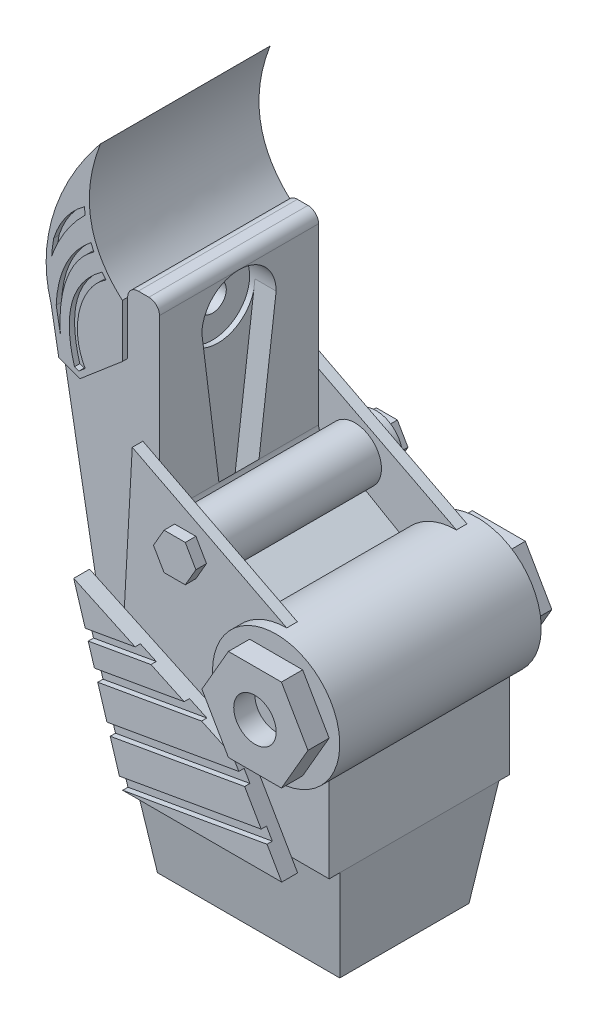
SolidWorks part; units mm, degrees
ref_plane "Front Plane" through (0, 0, 0) normal (0, 0, 1) x (1, 0, 0)
ref_plane "Top Plane" through (0, 0, 0) normal (0, 1, 0) x (1, 0, 0)
ref_plane "Right Plane" through (0, 0, 0) normal (1, 0, 0) x (0, 0, -1)
sketch "Sketch1" plane through (0, 0, 0) normal (0, 0, 1) x (1, 0, 0)
  line L0 (0, -1) -> (0, -17.4226)
  line L1 (0.5, -18.2887) -> (16.5, -27.5263)
  line L2 (17, -28.3923) -> (17, -38)
  line L3 (17, -38) -> (-3, -38)
  line L4 (-3, -38) -> (-3, -1)
  line L5 (-2, 0) -> (-1, 0)
  arc A0 (0, -17.4226) -> (0.5, -18.2887) centre (1, -17.4226) ccw
  arc A1 (16.5, -27.5263) -> (17, -28.3923) centre (16, -28.3923) cw
  arc A2 (0, -1) -> (-1, 0) centre (-1, -1) ccw
  arc A3 (-3, -1) -> (-2, 0) centre (-2, -1) cw
  point P9 (0, -18)
  point P14 (0, 0)
  point P17 (-3, 0)
  dimension "D6" = 1
  dimension "D1" = 3
  dimension "D2" = 18
  dimension "D3" = 120
  dimension "D4" = 20
  dimension "D5" = 38
extrude "Boss-Extrude1" add sketch "Sketch1" along normal blind 15
sketch "Sketch2" plane through (0, -38, 0) normal (0, -1, 0) x (1, 0, 0)
  line L6 (-3, 15) -> (17, 15)
  line L7 (-3, 15) -> (-3, 0)
  line L8 (-3, 0) -> (17, 0)
  line L9 (17, 15) -> (17, 0)
extrude "Boss-Extrude2" add sketch "Sketch2" along normal blind 10 draft 8
shell "Shell1" thickness 2
sketch "Sketch4" plane through (0, 0, 0) normal (1, 0, 0) x (0, 0, -1)
  line L0 (-15, -1) -> (0, -1) construction
  circle A0 centre (-7.5, -4.5) radius 1.3
  point P4 (-7.5, -1)
  dimension "D1" = 2.6
  dimension "D2" = 3.5
extrude "Cut-Extrude1" cut sketch "Sketch4" against normal through all
sketch "Sketch5" plane through (0, 0, 0) normal (1, 0, 0) x (0, 0, -1)
  line L1 (-4, -4.5) -> (-6, -20.5)
  line L16 (-11, -4.5) -> (-8.9885, -20.685)
  arc A0 (-4.1077, -5.3615) -> (-10.8935, -5.3567) centre (-7.5, -4.5) ccw
  arc A1 (-8.9885, -20.685) -> (-6, -20.5) centre (-7.5, -20.5) ccw
  point P8 (0, 0)
  point P9 (0, 0)
  circle M13 centre (-7.5, -4.5) radius 1.3
  line M17 (-15, -17.4226) -> (0, -17.4226)
  dimension "D1" = 7
  dimension "D2" = 3
  dimension "D3" = 16
extrude "Cut-Extrude2" cut sketch "Sketch5" against normal blind 2 contours A0 L16 L1 M17 M13 | L16 A1 L1 M17
sketch "Sketch20" plane through (-2, 0, 0) normal (1, 0, 0) x (0, 0, -1)
  circle A0 centre (-7.5, -4.5) radius 3.5
  dimension "D1" = 7
extrude "Cut-Extrude8" cut sketch "Sketch20" against normal blind 0.5
sketch "Sketch7" plane through (0, 0, 0) normal (0, 0, -1) x (-1, 0, 0)
  line L0 (-16.5, -27.5263) -> (-0.5, -18.2887) construction
  circle A0 centre (-13, -25.5056) radius 6
  dimension "D1" = 12
  dimension "D2" = 4
extrude "Boss-Extrude3" add sketch "Sketch7" along normal blind 2 and the other way blind 17
sketch "Sketch8" plane through (0, 0, -2) normal (0, 0, -1) x (-1, 0, 0)
  line L1 (-10.5, -21.1754) -> (-15.5, -21.1754)
  line L2 (-15.5, -21.1754) -> (-18, -25.5056)
  line L3 (-18, -25.5056) -> (-15.5, -29.8357)
  line L4 (-15.5, -29.8357) -> (-10.5, -29.8357)
  line L5 (-10.5, -29.8357) -> (-8, -25.5056)
  line L6 (-8, -25.5056) -> (-10.5, -21.1754)
  circle A0 centre (-13, -25.5056) radius 4.3301 construction
  dimension "D1" = 5
extrude "Boss-Extrude4" add sketch "Sketch8" along normal blind 2 and the other way blind 21
sketch "Sketch9" plane through (0, 0, -4) normal (0, 0, -1) x (-1, 0, 0)
  circle A0 centre (-13, -25.5056) radius 2
  dimension "D1" = 4
extrude "Cut-Extrude4" cut sketch "Sketch9" against normal blind 2
sketch "Sketch10" plane through (0, 0, 0) normal (0, 0, -1) x (-1, 0, 0)
  line L1 (1.5679, -12.0395) -> (3, -38)
  line L2 (3, -38) -> (-17, -38)
  line L3 (-17, -38) -> (-17, -29.9777)
  line L4 (-13, -19.5056) -> (1.5679, -12.0395)
  line L5 (3, -1) -> (3, -38) construction
  line L7 (-7.8038, -22.5056) -> (1.5679, -12.0395)
  arc A1 (-17, -29.9777) -> (-7.8038, -22.5056) centre (-13, -25.5056) ccw construction
  arc A2 (-17, -29.9777) -> (-7.8038, -22.5056) centre (-13, -25.5056) ccw
  circle A3 centre (-13, -25.5056) radius 6 construction
  arc A4 (-17, -29.9777) -> (-13, -19.5056) centre (-13, -25.5056) ccw
  line M17 (0, -1) -> (0, -17.4226)
  arc M18 (0, -17.4226) -> (-0.5, -18.2887) centre (-1, -17.4226) cw
  line M19 (-0.5, -18.2887) -> (-7.8038, -22.5056)
  dimension "D1" = 5.3396
  dimension "D2" = 26
  dimension "D3" = 1.4321
extrude "Boss-Extrude5" add sketch "Sketch10" along normal blind 1 contours A4 L4 M19 M18 M17
sketch "Sketch11" plane through (0, 0, -1) normal (0, 0, -1) x (-1, 0, 0)
  line L0 (-9.4117, -31) -> (-14.0274, -39)
  line L1 (-14.0274, -39) -> (0.9726, -39)
  line L2 (0.9726, -39) -> (5.5883, -24)
  line L3 (5.5883, -24) -> (-9.4117, -31)
  line L6 (3, -38) -> (-17, -38) construction
  line L7 (-17, -29.9777) -> (-17, -38) construction
  dimension "D1" = 15
  dimension "D2" = 1
  dimension "D3" = 145
  dimension "D4" = 8
  dimension "D5" = 15
  dimension "D6" = 15
  dimension "D7" = 2.9726
extrude "Boss-Extrude6" add sketch "Sketch11" along normal blind 1.5
sketch "Sketch12" plane through (0, 0, -2.5) normal (0, 0, -1) x (-1, 0, 0)
  line L0 (-12.6423, -36.5993) -> (0.9726, -39)
  line L3 (2.7386, -33.261) -> (1.2803, -38) construction
  line L4 (1.2803, -38) -> (-12.0902, -35.6424)
  line L7 (-14.0274, -39) -> (0.9726, -39) construction
  line L8 (-9.4117, -31) -> (-13.4504, -38) construction
  line L9 (-9.4117, -31) -> (-14.0274, -39) construction
  line L10 (1.2803, -38) -> (0.9726, -39)
  line L11 (-12.0902, -35.6424) -> (-12.6423, -36.5993)
  line L13 (-11.5869, -34.7701) -> (1.5608, -37.0885)
  line L14 (1.8685, -36.0885) -> (1.5608, -37.0885)
  line L15 (1.8685, -36.0885) -> (-11.0348, -33.8132)
  line L17 (-10.5316, -32.941) -> (2.149, -35.1769)
  line L18 (2.4567, -34.1769) -> (2.149, -35.1769)
  line L19 (2.4567, -34.1769) -> (-9.9795, -31.9841)
  line L21 (-9.4762, -31.1118) -> (2.7372, -33.2654)
  line L22 (3.0449, -32.2654) -> (2.7372, -33.2654)
  line L23 (3.0449, -32.2654) -> (-7.9637, -30.3242)
  line L25 (-6.4691, -29.6268) -> (3.3254, -31.3538)
  line L26 (3.6331, -30.3538) -> (3.3254, -31.3538)
  line L27 (3.6331, -30.3538) -> (-4.8295, -28.8616)
  line L29 (-3.3349, -28.1641) -> (3.9136, -29.4423)
  line L30 (4.2213, -28.4423) -> (3.9136, -29.4423)
  line L31 (4.2213, -28.4423) -> (-1.6953, -27.399)
  line L33 (-0.2007, -26.7015) -> (4.5018, -27.5307)
  line L34 (4.8095, -26.5307) -> (4.5018, -27.5307)
  line L35 (4.8095, -26.5307) -> (1.4389, -25.9364)
  line L37 (2.9335, -25.2389) -> (5.09, -25.6192)
  line L38 (5.3977, -24.6192) -> (5.09, -25.6192)
  line L39 (5.3977, -24.6192) -> (4.5731, -24.4738)
  line L44 (5.5883, -24) -> (-9.4117, -31)
  line L45 (-9.4117, -31) -> (-14.0274, -39)
  line L46 (-14.0274, -39) -> (0.9726, -39)
  line L47 (0.9726, -39) -> (5.5883, -24)
  line L48 (5.5883, -24) -> (-9.4117, -31)
  line L49 (-9.4117, -31) -> (-14.0274, -39)
  line L50 (-14.0274, -39) -> (0.9726, -39)
  line L51 (0.9726, -39) -> (5.5883, -24)
  line L52 (-11.502, -33.7309) -> (-12.0541, -34.6878) [skipped]
  line L53 (-10.9138, -31.8193) -> (-11.4659, -32.7762) [skipped]
  line L54 (-10.3256, -29.9078) -> (-10.8777, -30.8647) [skipped]
  line L55 (-9.7374, -27.9962) -> (-10.2895, -28.9531) [skipped]
  line L56 (-7.9728, -22.2616) -> (-8.5249, -23.2185) [skipped]
  line L57 (-8.561, -24.1731) -> (-9.1131, -25.13) [skipped]
  line L58 (-9.1492, -26.0847) -> (-9.7013, -27.0416) [skipped]
  line M33 (5.5883, -24) -> (-9.4117, -31)
  line M34 (-9.4117, -31) -> (-14.0274, -39)
  line M36 (0.9726, -39) -> (5.5883, -24)
  dimension "D1" = 10
  dimension "D2" = 1
  dimension "D5" = 1.3851
  dimension "D6" = 1.9372
  dimension "D7" = 1.9733
  dimension "D4" = 0
  dimension "D3" = 8
extrude "Cut-Extrude6" cut sketch "Sketch12" against normal blind 0.5 contours L4 L0 M36 M34 | L19 L17 M36 M34 | L27 L25 M36 M33 | L33 L31 M33 M36
sketch "Sketch15" plane through (0, 0, 0) normal (0, 0, -1) x (-1, 0, 0)
  line L0 (9.7251, -4.6332) -> (3.748, -38)
  line L1 (3.748, -38) -> (3, -38)
  line L2 (0, -12.843) -> (0, -1) construction
  line L3 (1, 0) -> (2, 0) construction
  line L4 (3, -1) -> (3, -38)
  spline S0 degree 2 poles (3, -1) (7.9187, 3.3061) (5.0735, 10.7299) knots 0 0 0 1 1 1
  spline S1 degree 3 poles (5.0735, 10.7299) (8.4361, 6.6499) (11.3497, 0.6864) (9.7251, -4.6332) knots 0 0 0 0 1 1 1 1
  dimension "D1" = 3.748
  dimension "D2" = 4.7072
  dimension "D3" = 5.0735
  dimension "D4" = 7.4207
  dimension "D5" = 9.7251
  dimension "D6" = 10.1092
  dimension "D7" = 0.9216
  dimension "D8" = 7.4012
  dimension "D9" = 10.7299
  dimension "D10" = 2.7981
  dimension "D11" = 4.6332
extrude "Boss-Extrude10" add sketch "Sketch15" against normal up to surface (15 mm away) up to face at (3.0002, -16.9768, 15)
sketch "Sketch16" plane through (0, 0, 0) normal (0, 0, -1) x (-1, 0, 0)
  line L0 (3, -1) -> (3, -6)
  line L1 (3, -6) -> (7, -9.4029)
  line L2 (7, -9.4029) -> (9, -8.6811)
  line L10 (0, -1) -> (0, -12.843)
  line L11 (0, -12.843) -> (1.5679, -12.0395)
  line L12 (1.5679, -12.0395) -> (3, -38)
  line L13 (3, -38) -> (3.748, -38)
  line L14 (3.748, -38) -> (9.7251, -4.6332)
  line L15 (2, 0) -> (1, 0)
  line L20 (0, -1) -> (0, -12.843)
  line L21 (0, -12.843) -> (1.5679, -12.0395)
  line L22 (1.5679, -12.0395) -> (3, -38)
  line L23 (3, -38) -> (3.748, -38)
  line L24 (3.748, -38) -> (9.7251, -4.6332)
  line L25 (2, 0) -> (1, 0)
  arc A2 (3, -1) -> (2, 0) centre (2, -1) ccw
  arc A3 (1, 0) -> (0, -1) centre (1, -1) ccw
  arc A4 (3, -1) -> (2, 0) centre (2, -1) ccw
  arc A5 (1, 0) -> (0, -1) centre (1, -1) ccw
  parabola Q1 (5.0735, 10.7299) -> (3, -1) focus (1.7401, 3.9502) apex (5.5085, 2.4369)
  parabola Q2 (5.0735, 10.7299) -> (3, -1) focus (1.7401, 3.9502) apex (5.5085, 2.4369)
  spline S1 degree 3 poles (-2748.1776, 1163.5808) (2734.394, -1537.3263) (-2585.0689, 1793.4008) (2349.8613, -1857.7679) knots -7.748836 -7.748836 -7.748836 -7.748836 9.519301 9.519301 9.519301 9.519301 only from (9.7251, -4.6332) to (5.0735, 10.7299)
  spline S2 degree 3 poles (9.7251, -4.6332) (11.3497, 0.6864) (8.4361, 6.6499) (5.0735, 10.7299) knots 0 0 0 0 1 1 1 1
  line M22 (3.748, -38) -> (9.7251, -4.6332)
  spline M23 degree 3 poles (9.7251, -4.6332) (11.3497, 0.6864) (8.4361, 6.6499) (5.0735, 10.7299) knots 0 0 0 0 1 1 1 1
  spline M24 degree 2 poles (5.0735, 10.7299) (7.9187, 3.3061) (3, -1) knots 0 0 0 1 1 1
  dimension "D2" = 5
  dimension "D3" = 4
  dimension "D4" = 120
  dimension "D5" = 2
  dimension "D6" = 5
  dimension "D1" = 0
extrude "Boss-Extrude11" add sketch "Sketch16" along normal blind 0.5 and the other way blind 15.5 contours L1 L2 L0 M22 M23 M24
sketch "Sketch17" plane through (0, 0, -0.5) normal (0, 0, -1) x (-1, 0, 0)
  line L0 (3.5, -1.2239) -> (3.5, -5.7689)
  line L1 (3.5, -5.7689) -> (7.1031, -8.8341)
  line L2 (7.1031, -8.8341) -> (8.5587, -8.3088)
  line L3 (8.5587, -8.3088) -> (9.2382, -4.5156)
  line L4 (3, -6) -> (7, -9.4029)
  line L5 (7, -9.4029) -> (9, -8.6811)
  line L6 (9, -8.6811) -> (9.7251, -4.6332)
  line L7 (3, -1) -> (3, -6)
  line L8 (3, -6) -> (7, -9.4029)
  line L9 (7, -9.4029) -> (9, -8.6811)
  line L10 (9, -8.6811) -> (9.7251, -4.6332)
  line L11 (3, -1) -> (3, -6)
  parabola Q1 (5.0735, 10.7299) -> (3, -1) focus (1.7401, 3.9502) apex (5.5085, 2.4369)
  parabola Q2 (5.0735, 10.7299) -> (3, -1) focus (1.7401, 3.9502) apex (5.5085, 2.4369)
  spline S0 degree 1 poles (9.2382, -4.5156) (6.3578, 8.154) knots 0 0 1 1 construction
  spline S1 degree 3 poles (-2748.1776, 1163.5808) (2734.394, -1537.3263) (-2585.0689, 1793.4008) (2349.8613, -1857.7679) knots -7.748836 -7.748836 -7.748836 -7.748836 9.519301 9.519301 9.519301 9.519301 only from (9.7251, -4.6332) to (5.0735, 10.7299)
  spline S2 degree 3 poles (9.7251, -4.6332) (11.3497, 0.6864) (8.4361, 6.6499) (5.0735, 10.7299) knots 0 0 0 0 1 1 1 1
  spline S3 degree 1 poles (6.3578, 8.154) (3.5, -1.2239) knots 0 0 1 1 construction
  spline S4 degree 3 poles (9.2382, -4.5156) (9.5335, -3.5488) (9.6975, -2.4063) (9.6847, -0.9949) (9.653, -0.4731) (9.5971, 0.0501) (9.5252, 0.5735) (9.4093, 1.2112) (9.0315, 2.8048) (8.1302, 5.2038) (6.989, 7.1987) (6.3578, 8.154) knots -0.001787 -0.001787 -0.001787 -0.001787 0.191835 0.216606 0.266149 0.290921 0.315692 0.365235 0.411651 0.61837 0.825089 0.825089 0.825089 0.825089
  spline S5 degree 3 poles (6.3578, 8.154) (6.4505, 7.6975) (6.5928, 6.757) (6.6291, 5.732) (6.5978, 5.0495) (6.5723, 4.745) (6.5484, 4.527) (6.5209, 4.3104) (6.4392, 3.7787) (6.2829, 3.1164) (6.062, 2.4703) (5.9225, 2.1252) (5.8305, 1.916) (5.7343, 1.7084) (5.5333, 1.3063) (5.2811, 0.8767) (5.0101, 0.4758) (4.8623, 0.2719) (4.7431, 0.1153) (4.6211, -0.04) (4.495, -0.1932) (4.1323, -0.6137) (3.8034, -0.9476) (3.5, -1.2239) knots 0.499337 0.499337 0.499337 0.499337 0.499481 0.499624 0.499672 0.499709 0.499727 0.499746 0.499783 0.499912 0.499982 0.500022 0.500042 0.500063 0.500103 0.5002 0.500236 0.500269 0.500286 0.500302 0.500336 0.500353 0.500487 0.500487 0.500487 0.500487
  spline S6 degree 2 poles (6.581, 4.8551) (8.6588, 3.3515) (9.4758, 0.8351) knots 0 0 0 1 1 1
  spline S7 degree 2 poles (6.5039, 4.2032) (8.6461, 2.1234) (9.6667, -0.7339) knots 0 0 0 1 1 1
  spline S8 degree 2 poles (5.9648, 2.2314) (9.0498, -0.2616) (9.2382, -4.5156) knots 0 0 0 1 1 1
  spline S9 degree 3 poles (5.6826, 1.6062) (8.2864, -0.189) (9.1024, -3.7584) (8.8381, -6.7492) knots 0 0 0 0 1 1 1 1
  spline S10 degree 2 poles (4.9194, 0.3513) (9.2396, -2.7636) (7.5156, -8.6853) knots 0 0 0 1 1 1
  spline S11 degree 3 poles (4.5577, -0.1165) (7.0934, -1.8032) (8.0251, -5.6898) (6.5039, -8.3244) knots 0 0 0 0 1 1 1 1
  dimension "D3" = 0.0584
  dimension "D4" = 0.2494
  dimension "D5" = 0.887
  dimension "D6" = 0.9348
  dimension "D7" = 2.8485
  dimension "D8" = 3.1441
  dimension "D9" = 3.7604
  dimension "D10" = 4.0426
  dimension "D11" = 1.8809
  dimension "D12" = 1.8809
  dimension "D13" = 2.2096
  dimension "D14" = 2.2096
  dimension "D15" = 2.622
  dimension "D16" = 4.8057
  dimension "D17" = 5.1675
  dimension "D18" = 0.4824
  dimension "D19" = 2.5443
  dimension "D20" = 3.2212
  dimension "D21" = 3.2212
  dimension "D22" = 3.3674
  dimension "D23" = 3.0025
  dimension "D24" = 4.8824
  dimension "D25" = 5.2636
  dimension "D26" = 7.3145
  dimension "D27" = 8.3531
  dimension "D28" = 2.0849
  dimension "D35" = 2.1161
  dimension "D1" = 0
  dimension "D2" = 0.5
extrude "Cut-Extrude7" cut sketch "Sketch17" against normal blind 0.5 contours S5 S11 L1 L2 S10 | S5 S9 L3 S8 | S5 S7 S4 S6
sketch "Sketch18" plane through (0, 0, -1) normal (0, 0, -1) x (-1, 0, 0)
  circle A0 centre (-3.4321, -18.0395) radius 2.5
  dimension "D1" = 5
  dimension "D2" = 5
  dimension "D3" = 6
extrude "Boss-Extrude12" add sketch "Sketch18" along normal blind 1 and the other way blind 17
sketch "Sketch19" plane through (0, 0, -2) normal (0, 0, -1) x (-1, 0, 0)
  line L1 (-1.4321, -18.0395) -> (-2.4321, -16.3074)
  line L2 (-2.4321, -16.3074) -> (-4.4321, -16.3074)
  line L3 (-4.4321, -16.3074) -> (-5.4321, -18.0395)
  line L4 (-5.4321, -18.0395) -> (-4.4321, -19.7715)
  line L5 (-4.4321, -19.7715) -> (-2.4321, -19.7715)
  line L6 (-2.4321, -19.7715) -> (-1.4321, -18.0395)
  circle A0 centre (-3.4321, -18.0395) radius 1.7321 construction
  dimension "D1" = 2
extrude "Boss-Extrude13" add sketch "Sketch19" along normal blind 1 and the other way blind 19
ref_plane "Plane1" through (0, 0, 7.5) normal (0, 0, 1) x (1, 0, 0)
mirror "Mirror1" about plane through (0, 0, 7.5) normal (0, 0, 1) of "Cut-Extrude4", "Boss-Extrude5", "Boss-Extrude6", "Cut-Extrude6", "Cut-Extrude7"
sketch "Sketch21" plane through (-3, 0, 0) normal (1, 0, 0) x (0, 0, -1)
  circle A1 centre (-7.5, -4.5) radius 1.3
  circle A2 centre (-7.5, -4.5) radius 1.3
  dimension "D1" = 0
extrude "Cut-Extrude9" cut sketch "Sketch21" against normal through all
